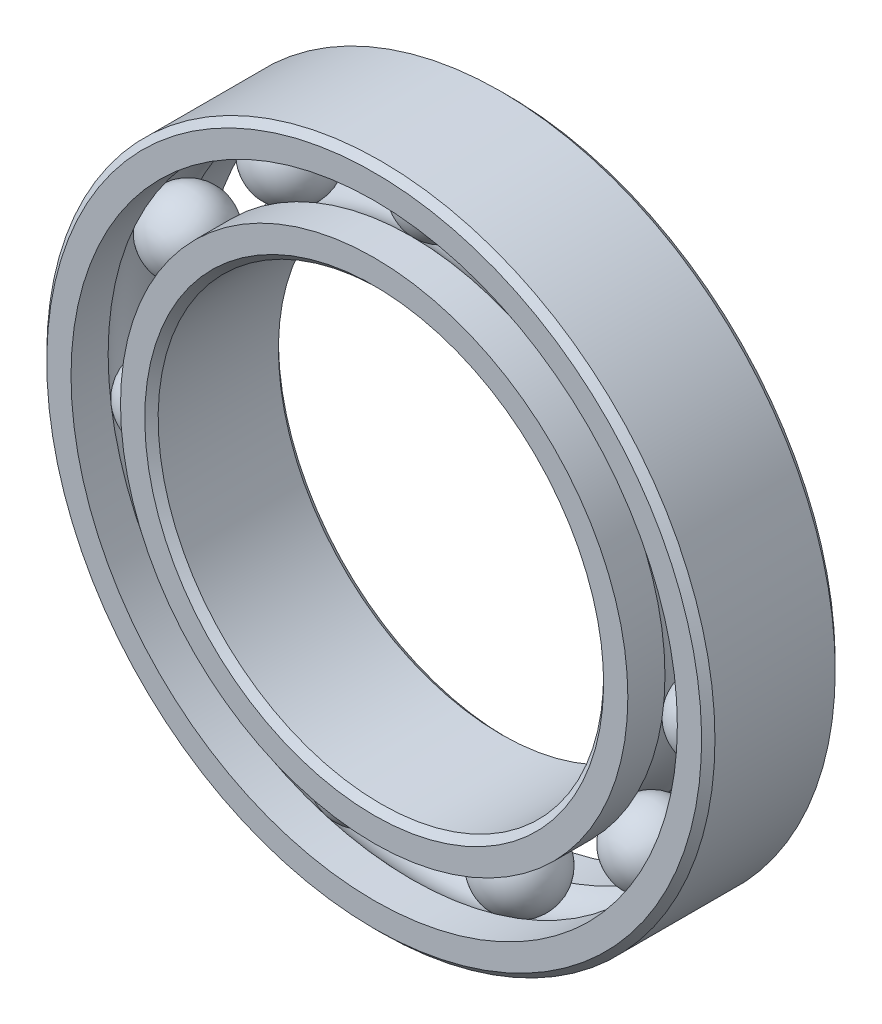
SolidWorks part; units mm, degrees
ref_plane "Front Plane" through (0, 0, 0) normal (0, 0, 1) x (1, 0, 0)
ref_plane "Top Plane" through (0, 0, 0) normal (0, 1, 0) x (1, 0, 0)
ref_plane "Right Plane" through (0, 0, 0) normal (1, 0, 0) x (0, 0, -1)
sketch "Sketch1" plane through (0, 0, 0) normal (0, 0, 1) x (1, 0, 0)
  circle A0 centre (0, 0) radius 7.5
  circle A1 centre (0, 0) radius 5
  dimension "OD" = 15
  dimension "ID" = 10
  dimension "For Shaft Diameter" = 10
  dimension "For Housing ID" = 15
sketch "Sketch5" plane through (0, 0, 0) normal (1, 0, 0) x (0, 0, -1)
  line L0 (-1.5, 0) -> (1.5, 0) construction
  line L1 (0, 7.5) -> (0, -7.5) construction
  line L2 (1.35, 7.5) -> (-1.35, 7.5)
  line L3 (-1.35, 7.5) -> (-1.5, 7.35)
  line L4 (-1.5, 7.35) -> (-1.5, 6.8056)
  line L5 (-1.5, 6.8056) -> (-0.6667, 6.8056)
  line L6 (1.5, 6.8056) -> (0.6667, 6.8056)
  line L7 (1.5, 7.35) -> (1.5, 6.8056)
  line L8 (1.35, 7.5) -> (1.5, 7.35)
  line L9 (0, 7.5) -> (0, 6.25) construction
  line L10 (0, 6.25) -> (0, 5) construction
  line L11 (-0.8678, 6.25) -> (-1.5, 6.25) construction
  line L12 (0.9934, 5.7198) -> (1.3744, 5.7198) construction
  line L13 (-0.9934, 5.7198) -> (-1.3744, 5.7198) construction
  line L14 (-0.9934, 5.7198) -> (-0.9934, 6.7802) construction
  line L15 (-0.9934, 6.7802) -> (-1.3744, 6.7802) construction
  line L16 (-1.3744, 5.7198) -> (-1.3744, 6.7802) construction
  line L17 (-0.9934, 5.7198) -> (-1.3744, 6.7802) construction
  line L18 (-0.9934, 6.7802) -> (-1.3744, 5.7198) construction
  line L19 (1.3744, 5.7198) -> (1.3744, 6.7802) construction
  line L20 (0.9934, 6.7802) -> (1.3744, 6.7802) construction
  line L21 (0.9934, 5.7198) -> (0.9934, 6.7802) construction
  line L22 (0, 7.5) -> (0, -7.5) construction
  arc A0 (-0.6667, 6.8056) -> (0.6667, 6.8056) centre (0, 6.25) cw
  circle A1 centre (0, 6.25) radius 0.8678 construction
  point P14 (0, 5)
  point P15 (-1.1839, 6.25)
  dimension "D1" = 45
  dimension "D2" = 0.15
  dimension "D3" = 1.3333
  dimension "D4" = 0.5556
  dimension "D5" = 0.381
  dimension "D6" = 0.0254
  dimension "Width" = 3
sketch "Sketch6" plane through (0, 0, 0) normal (1, 0, 0) x (0, 0, -1)
  line L0 (1.35, 7.5) -> (1.5, 7.35) construction
  line L1 (1.5, 7.35) -> (1.5, 6.8056) construction
  line L2 (1.5, 6.8056) -> (0.6667, 6.8056) construction
  line L3 (-1.5, 6.8056) -> (-0.6667, 6.8056) construction
  line L4 (-1.5, 7.35) -> (-1.5, 6.8056) construction
  line L5 (-1.35, 7.5) -> (-1.5, 7.35) construction
  line L6 (1.35, 7.5) -> (-1.35, 7.5) construction
  line L7 (1.35, 7.5) -> (1.5, 7.35)
  line L8 (1.5, 7.35) -> (1.5, 6.8056)
  line L9 (1.5, 6.8056) -> (0.6667, 6.8056)
  line L10 (-1.5, 6.8056) -> (-0.6667, 6.8056)
  line L11 (-1.5, 7.35) -> (-1.5, 6.8056)
  line L12 (-1.35, 7.5) -> (-1.5, 7.35)
  line L13 (1.35, 7.5) -> (-1.35, 7.5)
  arc A0 (0.6667, 6.8056) -> (-0.6667, 6.8056) centre (0, 6.25) ccw construction
  arc A1 (0.6667, 6.8056) -> (-0.6667, 6.8056) centre (0, 6.25) ccw
revolve "Revolve5" add sketch "Sketch6" angle 360 about L0
sketch "Sketch3" plane through (0, 0, 0) normal (1, 0, 0) x (0, 0, -1)
  line L0 (-1.5, 5.6944) -> (-0.6667, 5.6944)
  line L1 (0, 7.5) -> (0, -7.5) construction
  line L2 (-1.5, 7.35) -> (-1.5, 6.8056) construction
  line L3 (-1.5, 5.6944) -> (-1.5, 5.15)
  line L4 (-1.35, 7.5) -> (-1.5, 7.35) construction
  line L5 (-1.5, 5.15) -> (-1.35, 5)
  line L6 (-1.35, 5) -> (1.35, 5)
  line L8 (1.35, 5) -> (1.5, 5.15)
  line L10 (1.5, 5.15) -> (1.5, 5.6944)
  line L11 (1.5, 5.6944) -> (0.6667, 5.6944)
  line L12 (1.35, 7.5) -> (1.35, -7.5) construction
  line L13 (1.35, 7.5) -> (1.5, 7.35) construction
  line L14 (1.5, -7.35) -> (1.5, 7.35) construction
  arc A0 (0.6667, 6.8056) -> (-0.6667, 6.8056) centre (0, 6.25) ccw construction
  arc A1 (0.6667, 5.6944) -> (-0.6667, 5.6944) centre (0, 6.25) cw
revolve "Revolve3" add sketch "Sketch3" angle 360 about L0
sketch "Sketch4" plane through (0, 0, 0) normal (1, 0, 0) x (0, 0, -1)
  line L0 (-0.8678, 6.25) -> (0.8678, 6.25)
  arc A2 (-0.8678, 6.25) -> (0.8678, 6.25) centre (0, 6.25) cw
  arc A3 (0.6667, 6.8056) -> (-0.6667, 6.8056) centre (0, 6.25) ccw construction
revolve "Revolve4" add sketch "Sketch4" angle 360 about L0
pattern_circular "CirPattern1" count 11 over 360 about axis through (0, 0, 0) along (0, 0, 1) of bodies 104
equation "\"D2@Sketch5\" = \"Width@Sketch5\" * .05"
equation "\"D3@Sketch5\" = \"Width@Sketch5\" / 2.25"
equation "\"D4@Sketch5\"=((\"OD@Sketch1\"-\"ID@Sketch1\")/2)/4.5"
